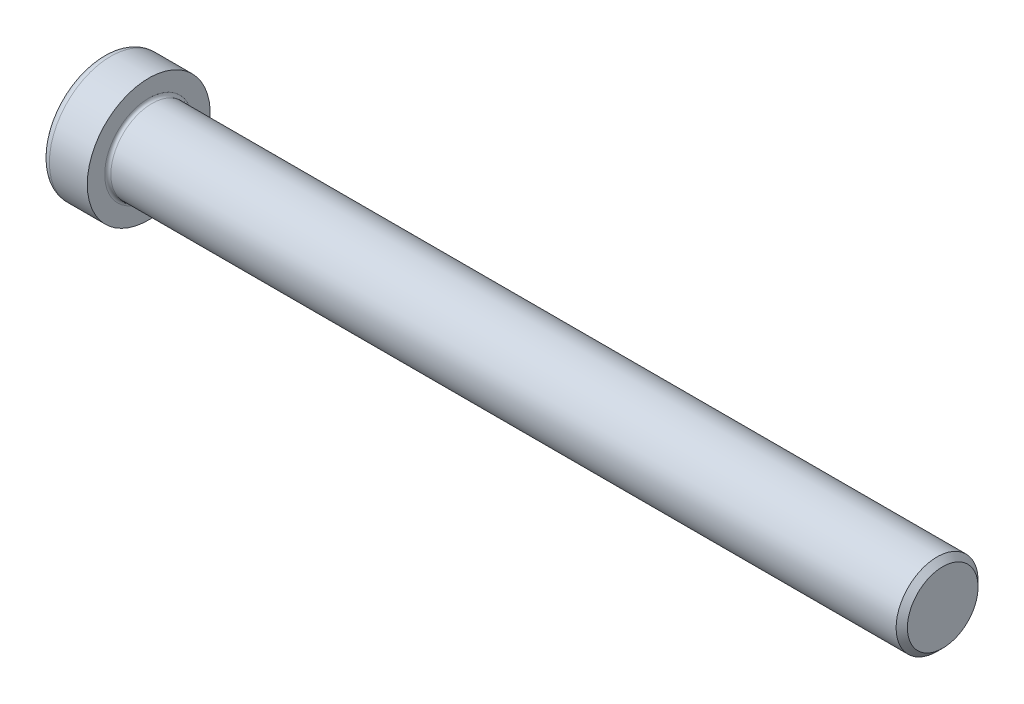
SolidWorks part; units mm, degrees
revolve "Base-Revolve" add sketch "BodySke"
sketch "BodySke" plane through (0, 0, 0) normal (0, 0, 1) x (1, 0, 0)
  line L0 (0, 0) -> (0, 12)
  line L1 (0, 12) -> (9, 12)
  line L2 (9, 12) -> (9, 8)
  line L3 (9, 8) -> (162.8985, 8)
  line L4 (164, 6.8985) -> (164, 0)
  line L5 (164, 0) -> (0, 0)
  line L6 (-31.75, 0) -> (127, 0) construction
  line L8 (164, 6.8985) -> (162.8985, 8)
  line L10 (164, -6.8985) -> (162.8985, -8) construction
  line L11 (11, 4.525) -> (11, -1.825) construction
  line L12 (104, 4.525) -> (104, -1.825) construction
  line L13 (84, 4.525) -> (84, -1.825) construction
  dimension "Head_ht" = 9
  dimension "Length" = 155
  dimension "Body_ch_ang" = 45
  dimension "Diameter" = 16
  dimension "Minor_dia" = 13.797
  dimension "Advance" = 2
  dimension "Thread_nom" = 60
  dimension "Thread_length" = 80
  dimension "Head_dia" = 24
cosmetic thread "ThreadCosmetic"
fillet "Fillet1" radius 0.6 1 edges at (9, 0, 8)
fillet "Fillet2" radius 1.6 1 edges at (0, 0, 12)
material "Сталь 20 ГОСТ 535-88"
ref_plane "Plane1" through (0, 0, 0) normal (0, 0, 1) x (1, 0, 0)
ref_plane "Plane2" through (0, 0, 0) normal (0, 1, 0) x (1, 0, 0)
ref_plane "Plane3" through (0, 0, 0) normal (1, 0, 0) x (0, 0, -1)
other "Configuration Table"
sketch "Sketch2" plane through (0, 0, 0) normal (0, 0, 1) x (1, 0, 0)
  line L0 (0, 6) -> (5.5, 6)
  line L1 (5.5, 6) -> (8.9641, 0)
  line L2 (-31.75, 0) -> (127, 0) construction
  line L3 (8.9641, 0) -> (0, 0)
  line L4 (0, 0) -> (0, 6)
  line L6 (0, 0) -> (47.625, 0) construction
  dimension "D1" = 6
  dimension "D2" = 60
  dimension "Depth" = 5.5
revolve "Hex-PreBroach" cut sketch "Sketch2" angle 360 about L6
sketch "Sketch3" plane through (0, 0, 0) normal (-1, 0, 0) x (0, 0.5, 0.866)
  line L0 (3.4641, 6) -> (-3.4641, 6)
  line L1 (-3.4641, 6) -> (-6.9282, 0)
  line L2 (3.4641, 6) -> (6.9282, 0)
  line L3 (3.4641, -6) -> (6.9282, 0)
  line L4 (3.4641, -6) -> (-3.4641, -6)
  line L5 (-3.4641, -6) -> (-6.9282, 0)
  dimension "D1" = 6
  dimension "Hex_size" = 12
extrude "Hex" cut sketch "Sketch3" against normal blind 5.5
sketch "ThdSchSke" plane through (0, 0, 0) normal (0, 0, 1) x (1, 0, 0)
  line L0 (104, -6.8985) -> (103.2287, -8)
  line L1 (104, -6.8985) -> (104.7713, -8)
  line L2 (104.7713, -8) -> (104.7713, -10)
  line L3 (-3.175, 0) -> (5.1513, 0) construction
  line L4 (0, 10.4) -> (0, -10.4) construction
  line L5 (104.7713, -10) -> (103.2287, -10)
  line L6 (103.2287, -10) -> (103.2287, -8)
  dimension "Thread_minor" = 13.797
  dimension "Diameter" = 16
  dimension "Start" = 104
revolve "ThreadSchematic" [suppressed] cut sketch "ThdSchSke" angle 360 about L3
pattern_linear "ThdSchPat" [suppressed]
equation "\"D2@Sketch3\" = \"Hex_size@Sketch3\" / 2"
equation "\"D1@Sketch3\" = \"Hex_size@Sketch3\" / 2"
equation "\"D1@Sketch2\" = \"Hex_size@Sketch3\" / 2"
equation "\"Thread_minor@ThreadCosmetic\"  =  \"Minor_dia@BodySke\""
equation "\"Depth@Sketch2\" =  \"Key_eng@Hex\""
equation "\"Thread_length@ThreadCosmetic\" = ((sgn( (\"Length@BodySke\" - \"Advance@BodySke\" * 3.0) - \"Thread_nom@BodySke\" )-1)*( (\"Length@BodySke\" - \"Advance@BodySke\" * 3.0) - \"Thread_nom@BodySke\" ))/-2+ \"Thread_nom@BodySke\""
equation "\"Thread_minor@ThdSchSke\" = \"Minor_dia@BodySke\""
equation "\"Diameter@ThdSchSke\" = \"Diameter@BodySke\""
equation "\"Overcut@ThdSchSke\" = \"Diameter@BodySke\" * 1.25"
equation "\"Start@ThdSchSke\" = \"Head_ht@BodySke\" + \"Length@BodySke\" - \"Thread_length@ThreadCosmetic\"  '---Non-countersunk---"
equation "\"Num_threads@ThdSchPat\" = int( \"Thread_length@ThreadCosmetic\" / \"Advance@BodySke\" + 0.999 )  + 1"
equation "\"Advance@ThdSchPat\" = \"Thread_length@ThreadCosmetic\" /  (\"Num_threads@ThdSchPat\" - 1) 'relax it"
equation "\"Num_threads@ThdSchPat\" = \"Num_threads@ThdSchPat\" - sgn( \"Num_threads@ThdSchPat\" - 1) '---chamfered tips only---"
